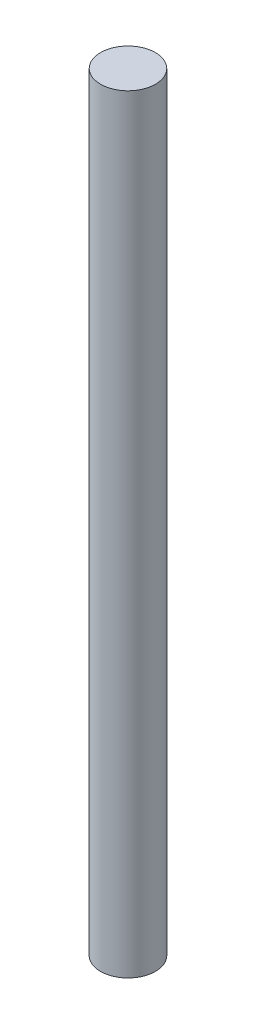
SolidWorks part; units mm, degrees
ref_plane "Front Plane" through (0, 0, 0) normal (0, 0, 1) x (1, 0, 0)
ref_plane "Top Plane" through (0, 0, 0) normal (0, 1, 0) x (1, 0, 0)
ref_plane "Right Plane" through (0, 0, 0) normal (1, 0, 0) x (0, 0, -1)
sketch "Sketch1" plane through (0, 0, 0) normal (0, 1, 0) x (1, 0, 0)
  circle A0 centre (0, 0) radius 2.5
  dimension "D1" = 5
extrude "Boss-Extrude1" add sketch "Sketch1" along normal blind 70
sketch "Sketch2" plane through (0, 70, 0) normal (0, 1, 0) x (1, 0, 0)
  circle A0 centre (0, 0) radius 2.5
